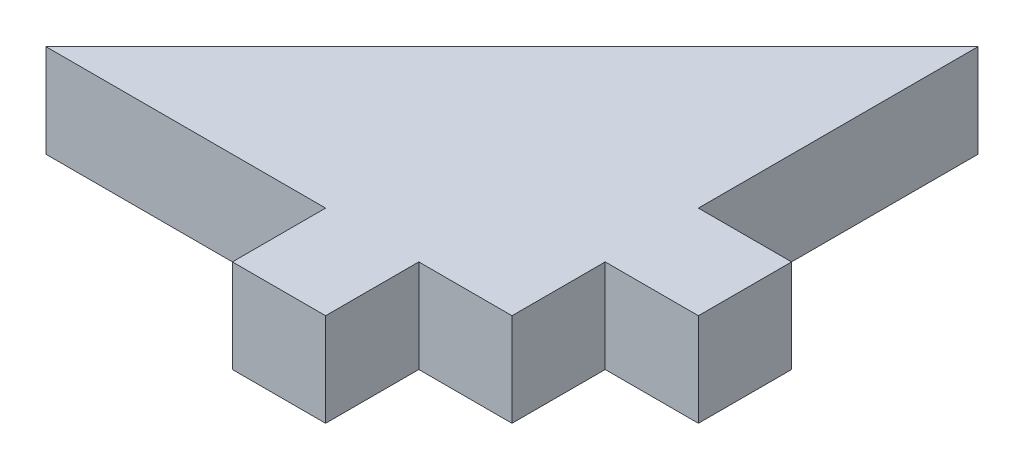
SolidWorks part; units mm, degrees
ref_plane "Front Plane" through (0, 0, 0) normal (0, 0, 1) x (1, 0, 0)
ref_plane "Top Plane" through (0, 0, 0) normal (0, 1, 0) x (1, 0, 0)
ref_plane "Right Plane" through (0, 0, 0) normal (1, 0, 0) x (0, 0, -1)
sketch "Sketch1" plane through (0, 0, 0) normal (0, 1, 0) x (1, 0, 0)
  line L0 (0, 0) -> (0, 12.7)
  line L1 (0, 12.7) -> (-12.7, 0)
  line L2 (-12.7, 0) -> (0, 0)
  dimension "D1" = 12.7
extrude "Boss-Extrude1" add sketch "Sketch1" along normal blind 2.54
sketch "Sketch2" plane through (0, 2.54, 0) normal (0, 1, 0) x (1, 0, 0)
  line L0 (-12.7, 0) -> (0, 0) construction
  line L1 (-5.08, 0) -> (-2.54, 0)
  line L2 (-5.08, 0) -> (-5.08, -2.54)
  line L3 (-5.08, -2.54) -> (-2.54, -2.54)
  line L4 (-2.54, 0) -> (-2.54, -2.54)
  line L5 (0, 0) -> (0, 12.7) construction
  line L6 (0, 5.08) -> (2.54, 5.08)
  line L7 (0, 5.08) -> (0, 2.54)
  line L8 (0, 2.54) -> (2.54, 2.54)
  line L9 (2.54, 5.08) -> (2.54, 2.54)
  dimension "D1" = 2.54
  dimension "D2" = 2.54
  dimension "D3" = 2.54
extrude "Boss-Extrude2" add sketch "Sketch2" against normal up to vertex (2.54 mm away)
